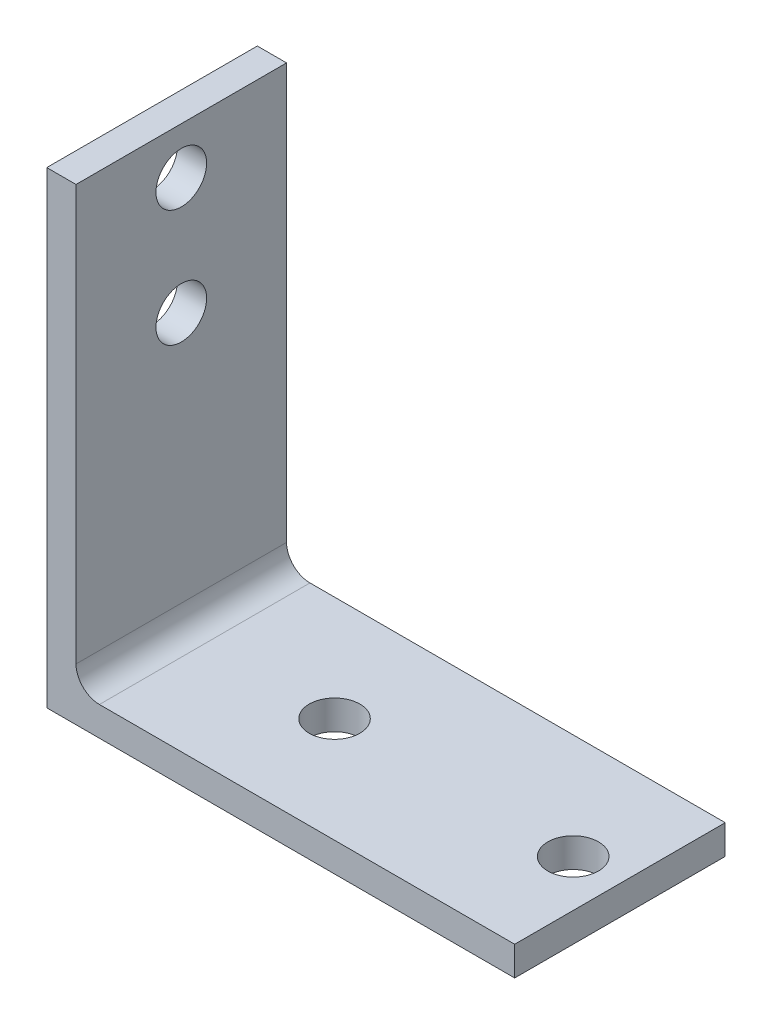
SolidWorks part; units mm, degrees
material "AISI 1010 Steel, hot rolled bar"
ref_plane "Frontal Plane" through (0, 0, 0) normal (0, 0, 1) x (1, 0, 0)
ref_plane "Horizontal Plane" through (0, 0, 0) normal (0, 1, 0) x (1, 0, 0)
ref_plane "Profile Plane" through (0, 0, 0) normal (1, 0, 0) x (0, 0, -1)
sketch "Sketch2" plane through (0, 0, 0) normal (0, 0, 1) x (1, 0, 0)
  line L0 (0, 0) -> (0, -50.8)
  line L1 (0, -50.8) -> (50.8, -50.8)
  line L2 (50.8, -50.8) -> (50.8, -47.625)
  line L3 (50.8, -47.625) -> (5.715, -47.625)
  line L4 (3.175, -45.085) -> (3.175, 0)
  line L5 (3.175, 0) -> (0, 0)
  arc A0 (5.715, -47.625) -> (3.175, -45.085) centre (5.715, -45.085) cw
  dimension "D4" = 2.54
  dimension "D1" = 50.8
  dimension "D2" = 50.8
  dimension "D3" = 3.175
extrude "Boss-Extrude1" add sketch "Sketch2" against normal mid plane 22.86
sketch "Sketch3" plane through (3.175, 0, 0) normal (1, 0, 0) x (0, 0, -1)
  line L0 (11.43, 0) -> (-11.43, 0) construction
  circle A0 centre (0, -5.08) radius 2.75
  circle A1 centre (0, -17.78) radius 2.75
  dimension "D1" = 5.5
  dimension "D2" = 12.7
  dimension "D3" = 5.08
extrude "Cut-Extrude1" cut sketch "Sketch3" against normal through all
sketch "Sketch4" plane through (0, -47.625, 0) normal (0, 1, 0) x (1, 0, 0)
  line L0 (50.8, 11.43) -> (50.8, -11.43) construction
  circle A0 centre (19.812, 0) radius 2.75
  circle A1 centre (45.72, 0) radius 2.75
  dimension "D1" = 5.5
  dimension "D2" = 25.908
  dimension "D3" = 5.08
extrude "Cut-Extrude2" cut sketch "Sketch4" against normal through all
